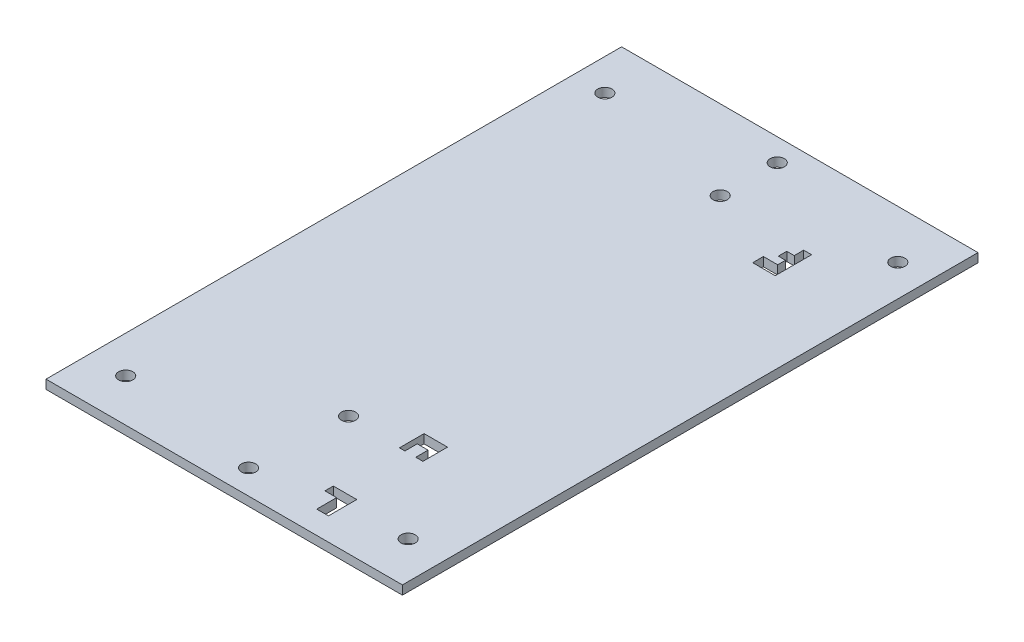
SolidWorks part; units mm, degrees
ref_plane "Front Plane" through (0, 0, 0) normal (0, 0, 1) x (1, 0, 0)
ref_plane "Top Plane" through (0, 0, 0) normal (0, 1, 0) x (1, 0, 0)
ref_plane "Right Plane" through (0, 0, 0) normal (1, 0, 0) x (0, 0, -1)
sketch "Sketch1" plane through (0, 0, 0) normal (0, 1, 0) x (1, 0, 0)
  line L0 (-100.6381, -96.0685) -> (100.6381, -96.0685) construction
  line L5 (100.6381, -96.0685) -> (0, 226.9665) construction
  line L6 (0, 226.9665) -> (-100.6381, -96.0685) construction
  line L7 (-100.6381, -96.0685) -> (0, 267.6095) construction
  line L8 (0, 267.6095) -> (100.6381, -96.0685) construction
  line L9 (-104.394, 249.1485) -> (3.6663, -41.5695) construction
  line L10 (-127, 283.6942) -> (127, 283.6942)
  line L11 (-127, 283.6942) -> (-127, -126.5158)
  line L12 (-127, -126.5158) -> (127, -126.5158)
  line L13 (127, 283.6942) -> (127, -126.5158)
  line L14 (3.6663, -41.5695) -> (104.394, 249.1485) construction
  line L15 (104.394, 249.1485) -> (-104.394, 249.1485) construction
  line L16 (-104.394, 249.1485) -> (0, -109.1377) construction
  line L17 (0, -109.1377) -> (104.394, 249.1485) construction
  line L18 (69.0129, 197.1736) -> (52.9485, 197.1736)
  line L19 (52.9485, 197.1736) -> (52.9485, 204.7982)
  line L20 (52.9485, 204.7982) -> (63.1353, 204.7982)
  line L21 (63.1353, 204.7982) -> (63.1353, 210.3547)
  line L22 (63.1353, 210.3547) -> (58.0419, 210.3547)
  line L24 (63.3668, 216.3742) -> (63.3668, 223.0882)
  line L25 (63.3668, 223.0882) -> (69.0129, 223.0882)
  line L26 (69.0129, 223.0882) -> (69.0129, 197.1736)
  line L27 (63.3668, 216.3742) -> (58.0419, 216.3742)
  line L28 (58.0419, 216.3742) -> (58.0419, 210.3547)
  line L29 (41.3457, -42.9514) -> (41.3457, -25.4104)
  line L30 (41.3457, -25.4104) -> (58.0419, -25.4104)
  line L31 (58.0419, -25.4104) -> (58.0419, -42.9514)
  line L32 (58.0419, -42.9514) -> (52.9485, -42.9514)
  line L33 (52.9485, -42.9514) -> (52.9485, -34.1809)
  line L34 (52.9485, -34.1809) -> (45.2394, -34.1809)
  line L35 (45.2394, -34.1809) -> (45.2394, -42.9514)
  line L36 (41.3457, -42.9514) -> (45.2394, -42.9514)
  line L37 (58.0419, -110.2615) -> (58.0419, -90.0939)
  line L38 (58.0419, -90.0939) -> (41.3457, -90.0939)
  line L39 (41.3457, -90.0939) -> (41.3457, -96.0685)
  line L40 (41.3457, -96.0685) -> (49.6938, -96.0685)
  line L41 (49.6938, -96.0685) -> (49.6938, -110.2615)
  line L42 (49.6938, -110.2615) -> (58.0419, -110.2615)
  line L43 (0, -96.0685) -> (0, 226.9665) construction
  circle A0 centre (-100.6381, -96.0685) radius 5.08
  circle A1 centre (100.6381, -96.0685) radius 5.08
  circle A2 centre (0, 226.9665) radius 5.08
  circle A3 centre (0, 267.6095) radius 5.08
  circle A4 centre (-104.394, 249.1485) radius 5.08
  circle A5 centre (104.394, 249.1485) radius 5.08
  circle A6 centre (3.6663, -41.5695) radius 5.08
  circle A7 centre (0, -109.1377) radius 5.08
  point P6 (0, 283.6942)
  point P13 (0, -96.0685)
  point P20 (0, 249.1485)
  dimension "D1" = 10.16
  dimension "D2" = 10.16
  dimension "D3" = 10.16
  dimension "D9" = 10.16
  dimension "D10" = 310.1516
  dimension "D15" = 254
  dimension "D4" = 338.3483
  dimension "D5" = 338.3483
  dimension "D6" = 100.6381
  dimension "D7" = 377.3455
  dimension "D8" = 377.3455
  dimension "D11" = 307.6736
  dimension "D12" = 104.394
  dimension "D13" = 373.1852
  dimension "D14" = 373.1852
  dimension "D16" = 410.21
extrude "Boss-Extrude1" add sketch "Sketch1" along normal blind 6.35
